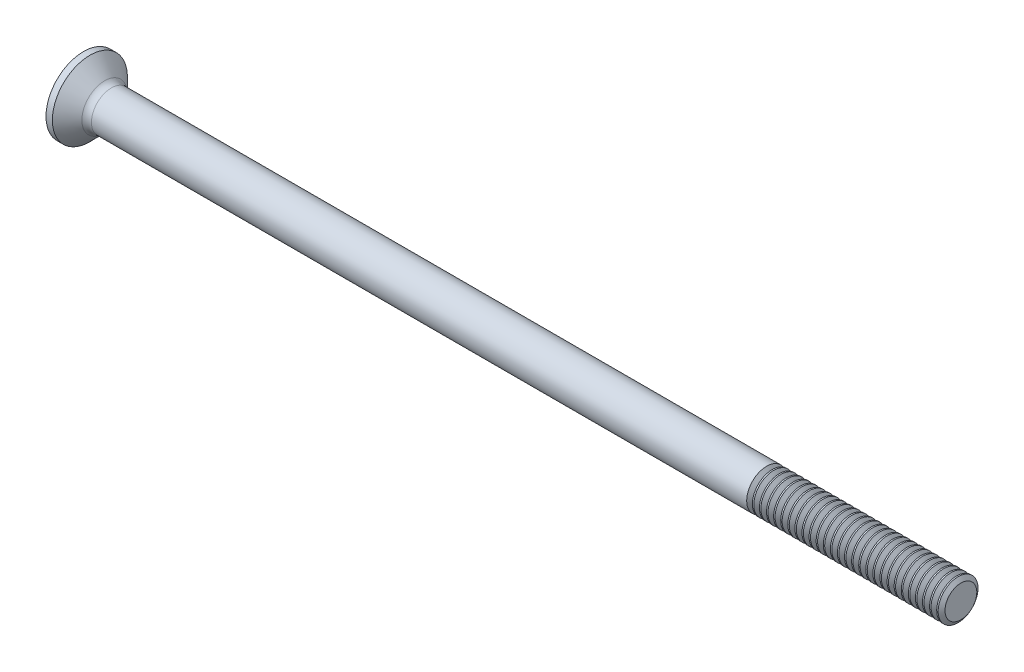
SolidWorks part; units mm, degrees
ref_plane "Plane1" through (0, 0, 0) normal (0, 0, 1) x (1, 0, 0)
ref_plane "Plane2" through (0, 0, 0) normal (0, 1, 0) x (1, 0, 0)
ref_plane "Plane3" through (0, 0, 0) normal (1, 0, 0) x (0, 0, -1)
sketch "BodySke" plane through (0, 0, 0) normal (0, 0, 1) x (1, 0, 0)
  line L0 (0, 0) -> (0, 2.35)
  line L1 (0, 2.35) -> (0.4, 2.35)
  line L2 (1.5, 1.25) -> (55, 1.25)
  line L3 (55, 1.25) -> (55, 0)
  line L4 (55, 0) -> (0, 0)
  line L5 (-6.35, 0) -> (82.55, 0) construction
  line L6 (1.5, -1.25) -> (55, -1.25) construction
  line L7 (0.4, -2.35) -> (1.5, -1.25) construction
  line L8 (0.4, 2.35) -> (1.5, 1.25)
  line L9 (0, -2.35) -> (0.4, -2.35) construction
  line L10 (1.95, 2.8375) -> (1.95, -6.6875) construction
  line L11 (43, 6.35) -> (43, -3.175) construction
  dimension "Diameter" = 2.5
  dimension "Length" = 55
  dimension "Head_ht" = 1.5
  dimension "Head_dia" = 4.7
  dimension "Head_ang" = 90
  dimension "D6" = 0.4
  dimension "Advance" = 0.45
  dimension "Thread_nom" = 12
revolve "Base-Revolve" add sketch "BodySke"
cosmetic thread "ThreadCosmetic" [suppressed]
fillet "Fillet1" radius 0.6 1 edges at (1.5, 0, 1.25)
sketch "Sketch3" plane through (0, 0, 0) normal (-1, 0, 0) x (0, 0, 1)
  line L0 (-0.37, 1.4) -> (0.37, 1.4)
  line L1 (0.37, 1.4) -> (0.37, -1.4)
  line L2 (0.37, -1.4) -> (-0.37, -1.4)
  line L3 (-0.37, -1.4) -> (-0.37, 1.4)
  dimension "D1" = 1.4
  dimension "Cross_dia" = 2.8
  dimension "D2" = 0.37
  dimension "Cross_width" = 0.74
ref_plane "Plane4" through (1.73, 0, 0) normal (-1, 0, 0) x (0, 0, 1)
sketch "Sketch4" plane through (1.73, 0, 0) normal (-1, 0, 0) x (0, 0, 1)
  line L0 (-0.37, 0.5375) -> (0.37, 0.5375)
  line L3 (0.37, 0.5375) -> (0.37, -0.5375)
  line L4 (0.37, -0.5375) -> (-0.37, -0.5375)
  line L5 (-0.37, -0.5375) -> (-0.37, 0.5375)
  dimension "D1" = 0.74
  dimension "D2" = 1.0749
  dimension "D3" = 0.37
  dimension "D4" = 0.5375
loft "Recess" cut profiles "Sketch3", "Sketch4"
pattern_circular "RecPat" count 2 every 90 about axis through (0, 0, 0) along (1, 0, 0) of "Recess"
sketch "RecCorSke" plane through (0, 0, 0) normal (0, 0, 1) x (1, 0, 0)
  line L0 (-3.175, 0) -> (15.875, 0) construction
  line L2 (0, 0) -> (0, 0.677)
  line L3 (0, 0.677) -> (1.73, 0.556)
  line L4 (1.73, 0.556) -> (1.9107, 0)
  line L5 (1.9107, 0) -> (0, 0)
  dimension "Diameter" = 1.112
  dimension "Depth" = 1.73
  dimension "Draft_angle" = 4
  dimension "Bottom_angle" = 18
revolve "RecessCore" cut sketch "RecCorSke" angle 360 about L0
sketch "ThdSchSke" plane through (0, 0, 0) normal (0, 0, 1) x (1, 0, 0)
  line L0 (43, -0.9965) -> (42.8225, -1.25)
  line L1 (43, -0.9965) -> (43.1775, -1.25)
  line L2 (43.1775, -1.25) -> (43.1775, -1.5625)
  line L3 (-3.175, 0) -> (5.1513, 0) construction
  line L5 (43.1775, -1.5625) -> (42.8225, -1.5625)
  line L6 (42.8225, -1.5625) -> (42.8225, -1.25)
  line L7 (0, 2.35) -> (0, -2.35) construction
  dimension "Thread_minor" = 1.993
  dimension "Diameter" = 2.5
  dimension "Start" = 43
  dimension "SideAngle" = 55
  dimension "VeeAngle" = 70
  dimension "Overcut" = 3.125
revolve "ThreadSchematic" cut sketch "ThdSchSke" angle 360 about L3
pattern_linear "ThdSchPat" count 28 spacing 0.4444 along (1, 0, 0) of "ThreadSchematic"
equation "\"D1@Sketch3\" = \"Cross_dia@Sketch3\" / 2"
equation "\"D2@Sketch3\" = \"Cross_width@Sketch3\" / 2"
equation "\"Depth@RecCorSke\" = \"Cross_depth@Plane4\""
equation "\"D1@Sketch4\" = \"Cross_width@Sketch3\""
equation "\"D2@Sketch4\" = \"Cross_dia@Sketch3\" - 2.0 * \"Cross_depth@Plane4\" * tan(26.5  * 0.017453292)"
equation "\"D3@Sketch4\" = \"D1@Sketch4\" / 2"
equation "\"D4@Sketch4\" = \"D2@Sketch4\" / 2"
equation "\"Thread_length@ThreadCosmetic\" = ((sgn( (\"Length@BodySke\" - \"Advance@BodySke\" * 1.0 - \"Head_ht@BodySke\" ) - \"Thread_nom@BodySke\" )-1)*( (\"Length@BodySke\" - \"Advance@BodySke\" * 1.0 - \"Head_ht@BodySke\" ) - \"Thread_nom@BodySke\" ))/-2+ \"Thread_nom@BodySke\""
equation "\"Thread_minor@ThdSchSke\" = \"Thread_minor@ThreadCosmetic\""
equation "\"Diameter@ThdSchSke\" = \"Diameter@BodySke\""
equation "\"Overcut@ThdSchSke\" = \"Diameter@BodySke\" * 1.25"
equation "\"Start@ThdSchSke\" = 0.000001 + \"Length@BodySke\" - \"Thread_length@ThreadCosmetic\"  '---Countersunk---"
equation "\"Num_threads@ThdSchPat\" = int( \"Thread_length@ThreadCosmetic\" / \"Advance@BodySke\" + 0.999 )  + 1"
equation "\"Advance@ThdSchPat\" = \"Thread_length@ThreadCosmetic\" /  (\"Num_threads@ThdSchPat\" - 1) 'relax it"
